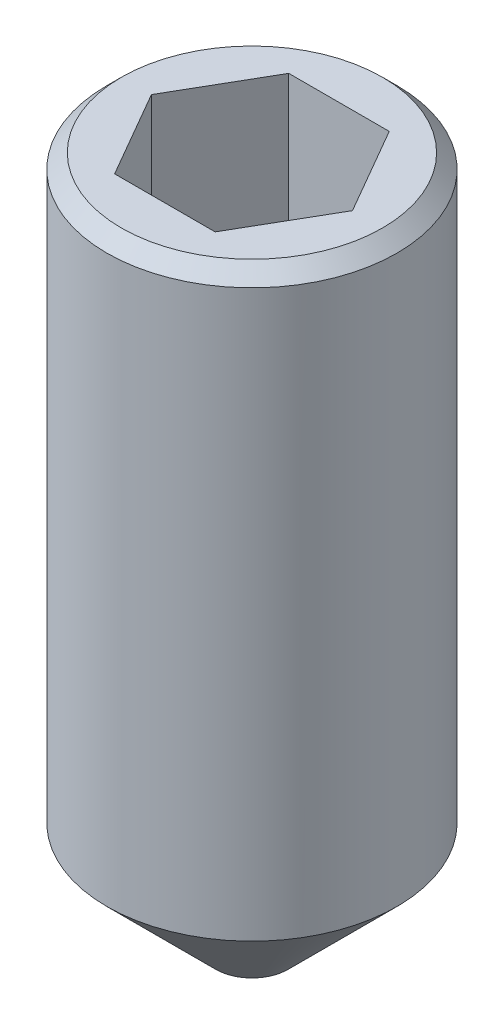
SolidWorks part; units mm, degrees
ref_plane "前视基准面" through (0, 0, 0) normal (0, 0, 1) x (1, 0, 0)
ref_plane "上视基准面" through (0, 0, 0) normal (0, 1, 0) x (1, 0, 0)
ref_plane "右视基准面" through (0, 0, 0) normal (1, 0, 0) x (0, 0, -1)
sketch "草图1" plane through (0, 0, 0) normal (0, 0, 1) x (1, 0, 0)
  line L0 (0, 0) -> (1, 0)
  line L1 (1, 0) -> (1, -4)
  line L2 (1, -4) -> (0.25, -4.75)
  line L3 (0, -4.75) -> (0, 0)
  line L4 (0, 8.7135) -> (0, -8.7135) construction
  line L5 (0.25, -4.75) -> (0, -4.75)
  point P10 (0, 0)
  dimension "D1" = 2
  dimension "D2" = 4
  dimension "D3" = 0.75
  dimension "D4" = 0.5
revolve "旋转1" add sketch "草图1" angle 360 about L4
sketch "草图2" plane through (0, 0, 0) normal (0, 1, 0) x (1, 0, 0)
  line L1 (-0.3464, -0.6) -> (0.3464, -0.6)
  line L2 (0.3464, -0.6) -> (0.6928, 0)
  line L3 (0.6928, 0) -> (0.3464, 0.6)
  line L4 (0.3464, 0.6) -> (-0.3464, 0.6)
  line L5 (-0.3464, 0.6) -> (-0.6928, 0)
  line L6 (-0.6928, 0) -> (-0.3464, -0.6)
  circle A0 centre (0, 0) radius 0.6 construction
  dimension "D1" = 1.2
extrude "切除-拉伸1" cut sketch "草图2" against normal blind 1.5
chamfer "倒角1" distance 0.1 angle 45 1 edges at (0, 0, 1)
